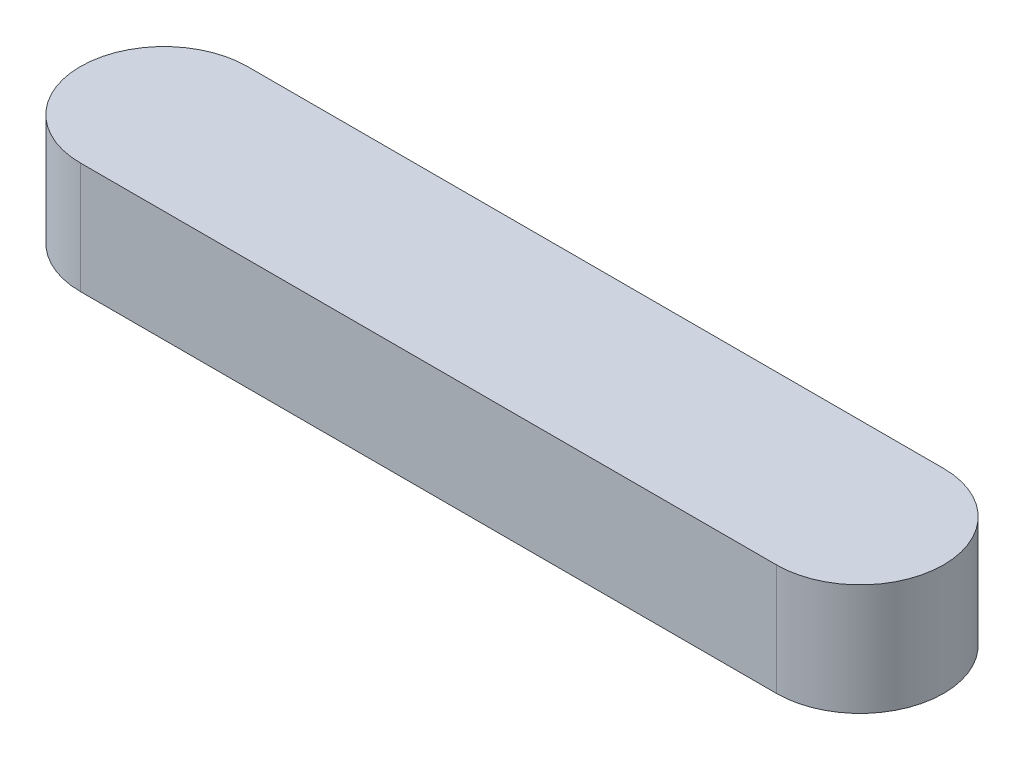
SolidWorks part; units mm, degrees
ref_plane "Front Plane" through (0, 0, 0) normal (0, 0, 1) x (1, 0, 0)
ref_plane "Top Plane" through (0, 0, 0) normal (0, 1, 0) x (1, 0, 0)
ref_plane "Right Plane" through (0, 0, 0) normal (1, 0, 0) x (0, 0, -1)
sketch "Sketch1" plane through (0, 0, 0) normal (0, 1, 0) x (1, 0, 0)
  line L0 (0, 0) -> (25, 0) construction
  line L1 (0, 3) -> (25, 3)
  line L2 (0, -3) -> (25, -3)
  arc A0 (0, 3) -> (0, -3) centre (0, 0) ccw
  arc A1 (25, -3) -> (25, 3) centre (25, 0) ccw
  point P3 (12.5, 0)
  dimension "D1" = 25
  dimension "D2" = 6
extrude "Boss-Extrude1" add sketch "Sketch1" along normal blind 4
